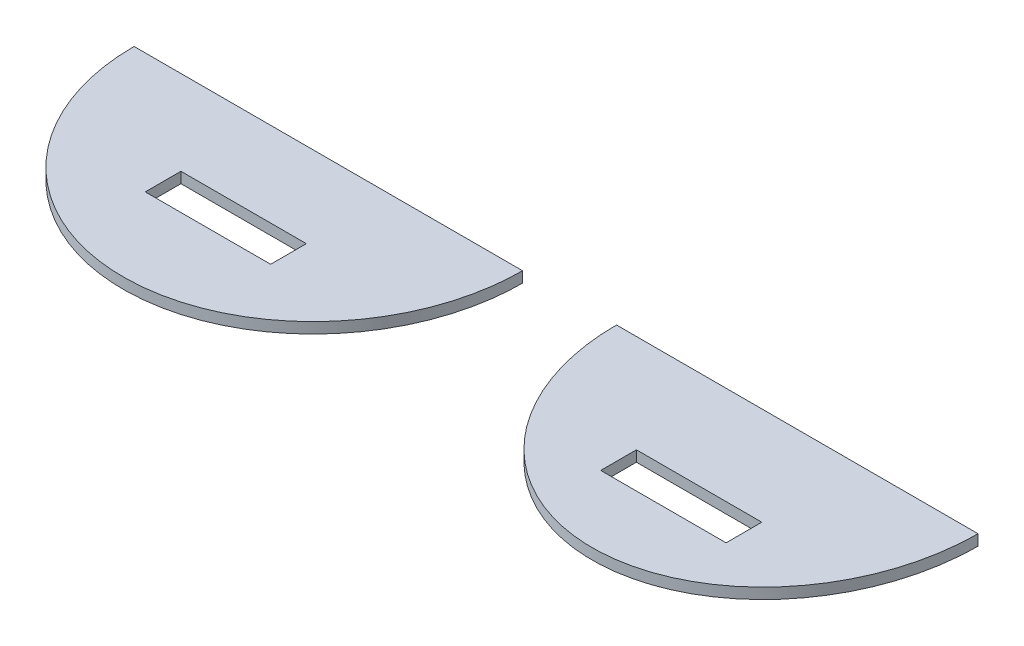
SolidWorks part; units mm, degrees
ref_plane "Front Plane" through (0, 0, 0) normal (0, 0, 1) x (1, 0, 0)
ref_plane "Top Plane" through (0, 0, 0) normal (0, 1, 0) x (1, 0, 0)
ref_plane "Right Plane" through (0, 0, 0) normal (1, 0, 0) x (0, 0, -1)
sketch "Sketch2" plane through (0, 0, 0) normal (0, 1, 0) x (1, 0, 0)
  line L4 (-118.1787, 115.0893) -> (-118.1787, 106.6819)
  line L5 (-118.1787, 115.0893) -> (-88.6639, 115.0893)
  line L6 (-88.6639, 115.0893) -> (-88.6639, 106.6819)
  line L7 (-88.6639, 106.6819) -> (-118.1787, 106.6819)
  line L8 (-149.1413, 135.0156) -> (-57.7013, 135.0156)
  line L9 (49.5088, 135.0156) -> (-35.5812, 135.0156)
  line L10 (-7.7936, 111.9143) -> (-7.7936, 103.5069)
  line L12 (-7.7936, 111.9143) -> (21.7212, 111.9143)
  line L13 (21.7212, 111.9143) -> (21.7212, 103.5069)
  line L14 (21.7212, 103.5069) -> (-7.7936, 103.5069)
  ellipse E0 centre (6.9638, 135.0156) end of major axis (6.9638, 86.7556) minor radius 42.545 (-35.5812, 135.0156) -> (49.5088, 135.0156) ccw
  ellipse E1 centre (-103.4213, 135.0156) end of major axis (-103.4213, 183.2756) minor radius 45.72 (-149.1413, 135.0156) -> (-57.7013, 135.0156) ccw
other "AlignGroup1"
extrude "Boss-Extrude2" add sketch "Sketch2" along normal blind 2.54
